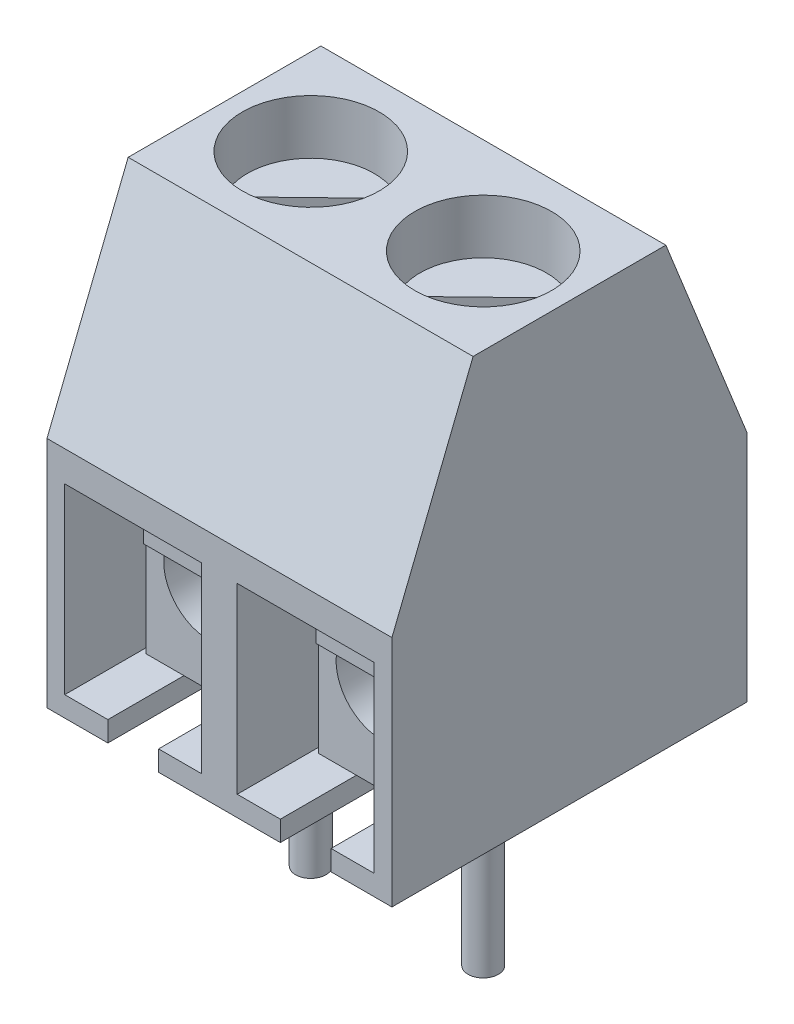
SolidWorks part; units mm, degrees
ref_plane "Plan de face" through (0, 0, 0) normal (0, 0, 1) x (1, 0, 0)
ref_plane "Plan de dessus" through (0, 0, 0) normal (0, 1, 0) x (1, 0, 0)
ref_plane "Plan de droite" through (0, 0, 0) normal (1, 0, 0) x (0, 0, -1)
sketch "Esquisse1" plane through (0, 0, 0) normal (1, 0, 0) x (0, 0, -1)
  line L0 (0, 0) -> (0, 4.6)
  line L1 (0, 4.6) -> (1.6, 8.6)
  line L2 (1.6, 8.6) -> (5.4, 8.6)
  line L3 (7, 4.6) -> (7, 0)
  line L4 (7, 0) -> (0, 0)
  line L5 (5.4, 8.6) -> (7, 4.6)
  line L6 (3.5, 0) -> (3.5, 8.6) construction
  dimension "D1" = 7
  dimension "D2" = 8.6
  dimension "D3" = 3.8
  dimension "D4" = 4
extrude "Boss.-Extru.1" add sketch "Esquisse1" along normal blind 3.4
sketch "Esquisse2" plane through (0, 0, 0) normal (0, 0, 1) x (1, 0, 0)
  line L0 (1.7, 0) -> (1.7, 0.4) construction
  line L1 (0.35, 0.4) -> (1.2, 0.4)
  line L2 (0.35, 0.4) -> (0.35, 4)
  line L3 (0.35, 4) -> (3.05, 4)
  line L4 (3.05, 0.4) -> (3.05, 4)
  line L5 (3.4, 0) -> (0, 0) construction
  line L6 (1.2, 0.4) -> (1.2, 0)
  line L7 (2.2, 0.4) -> (2.2, 0)
  line L8 (2.2, 0.4) -> (3.05, 0.4)
  line L9 (1.2, 0.4) -> (2.2, 0.4) construction
  line L10 (1.2, 0) -> (2.2, 0)
  dimension "D1" = 2.7
  dimension "D2" = 3.6
  dimension "D3" = 0.4
  dimension "D4" = 1
extrude "Enlèv. mat.-Extru.1" cut sketch "Esquisse2" against normal blind 6
sketch "Esquisse3" plane through (0, 8.6, 0) normal (0, 1, 0) x (1, 0, 0)
  line L0 (0, 5.4) -> (3.4, 1.6) construction
  line L1 (3.4, 5.4) -> (0, 1.6) construction
  circle A0 centre (1.7, 3.5) radius 1.35
  dimension "D1" = 2.7
extrude "Enlèv. mat.-Extru.2" cut sketch "Esquisse3" against normal up to next
sketch "Esquisse4" plane through (0, 8.6, 0) normal (0, 1, 0) x (1, 0, 0)
  circle A0 centre (1.7, 3.5) radius 1.25
  dimension "D1" = 2.5
extrude "Boss.-Extru.2" add sketch "Esquisse4" against normal blind 3.4 from offset 1 separate body offset against normal yes
sketch "Esquisse5" plane through (0, 7.6, 0) normal (0, 1, 0) x (1, 0, 0)
  line L0 (0.6187, 2.8729) -> (2.3645, 4.5587)
  line L1 (2.7813, 4.1271) -> (1.0355, 2.4413)
  line L2 (2.3645, 4.5587) -> (1.0355, 2.4413) construction
  line L3 (2.7813, 4.1271) -> (0.6187, 2.8729) construction
  line L4 (1.7, 3.5) -> (1.7, 5.2577) construction
  circle A0 centre (1.7, 3.5) radius 1.25 construction
  arc A1 (0.6187, 2.8729) -> (1.0355, 2.4413) centre (1.7, 3.5) ccw
  arc A2 (2.3645, 4.5587) -> (2.7813, 4.1271) centre (1.7, 3.5) cw
  dimension "D1" = 0.6
  dimension "D2" = 46
extrude "Enlèv. mat.-Extru.3" cut sketch "Esquisse5" against normal blind 0.4
sketch "Esquisse6" plane through (0, 0, 0) normal (0, 0, 1) x (1, 0, 0)
  line L0 (0.35, 0.4) -> (1.2, 0.4) construction
  line L1 (0.45, 0.4) -> (2.95, 0.4)
  line L2 (0.45, 0.4) -> (0.45, 3.9)
  line L3 (0.45, 3.9) -> (0.95, 3.9)
  line L4 (2.95, 0.4) -> (2.95, 3.9)
  line L5 (3.05, 4) -> (0.35, 4) construction
  line L7 (0.45, 3.9) -> (2.95, 0.4) construction
  line L8 (0.95, 3.9) -> (0.95, 3.65)
  line L9 (0.95, 3.65) -> (2.45, 3.65)
  line L10 (2.45, 3.65) -> (2.45, 3.9)
  line L11 (1.7, 2.15) -> (1.7, 4) construction
  line L12 (2.45, 3.9) -> (2.95, 3.9)
  circle A0 centre (1.7, 2.15) radius 0.9
  dimension "D3" = 1.8
  dimension "D1" = 3.5
  dimension "D2" = 2.5
  dimension "D4" = 1.5
  dimension "D5" = 0.25
extrude "Boss.-Extru.3" add sketch "Esquisse6" against normal up to surface (4.5 mm away) from offset 1.5 separate body up to face at (1.7, 1.2, -6) offset against normal yes
sketch "Esquisse7" plane through (0, 0.4, 0) normal (0, -1, 0) x (1, 0, 0)
  line L0 (1.7, -1.5) -> (1.7, -3.5) construction
  line L1 (0.45, -1.5) -> (2.95, -1.5) construction
  line L2 (1.2, 0) -> (0, 0) construction
  circle A0 centre (1.7, -3.5) radius 0.3
  dimension "D1" = 0.6
  dimension "D2" = 3.5
extrude "Boss.-Extru.4" add sketch "Esquisse7" along normal blind 4
ref_plane "Plan1" through (1.7, 0, 0) normal (1, 0, 0) x (0, 0, -1)
sketch "Esquisse8" plane through (1.7, 0, 0) normal (1, 0, 0) x (0, 0, -1)
  line L0 (2.15, 3.8) -> (1.5, 3.8)
  line L1 (1, 3.3) -> (1, 2.9)
  line L2 (1, 2.9) -> (2.4555, 1.6787)
  line L3 (2.15, 8.6) -> (2.15, 4) construction
  line L4 (6, 3.65) -> (1.5, 3.65) construction
  line L5 (1.5, 0.4) -> (1.5, 3.9) construction
  arc A0 (1.5, 3.8) -> (1, 3.3) centre (1.5, 3.3) ccw
  dimension "D2" = 0.5
  dimension "D1" = 0.15
  dimension "D3" = 0.4
  dimension "D4" = 1.9
  dimension "D5" = 130
extrude "Extru.-Mince1" add sketch "Esquisse8" along normal mid plane 1.4 separate body thin thin type mid plane wall 0.2
pattern_linear "Répétition linéaire2" count 2 spacing 3.4 along (1, 0, 0) of "Boss.-Extru.1", "Enlèv. mat.-Extru.2", "Enlèv. mat.-Extru.1"
pattern_linear "Répétition linéaire3" count 2 spacing 3.4 along (1, 0, 0) of bodies 105 108 107
